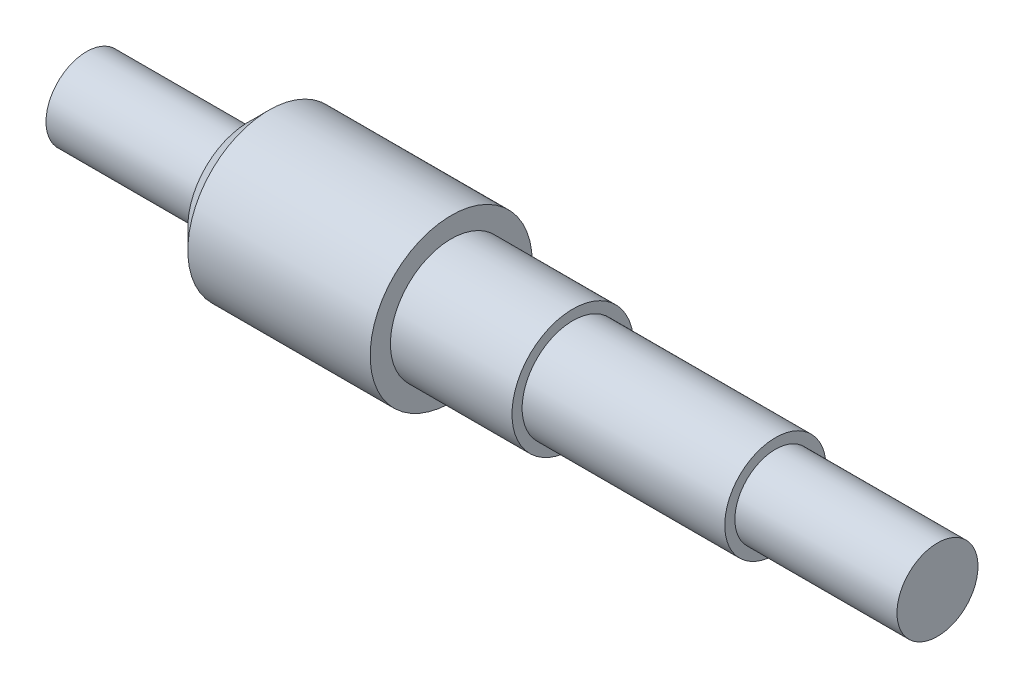
SolidWorks part; units mm, degrees
ref_plane "前视基准面" through (0, 0, 0) normal (0, 0, 1) x (1, 0, 0)
ref_plane "上视基准面" through (0, 0, 0) normal (0, 1, 0) x (1, 0, 0)
ref_plane "右视基准面" through (0, 0, 0) normal (1, 0, 0) x (0, 0, -1)
sketch "草图1" plane through (0, 0, 0) normal (1, 0, 0) x (0, 0, -1)
  circle A0 centre (0, 0) radius 4
  dimension "D1" = 8
extrude "凸台-拉伸1" add sketch "草图1" along normal blind 10
sketch "草图2" plane through (0, 0, 0) normal (-1, 0, 0) x (0, 0, 1)
  circle A0 centre (0, 0) radius 2
  dimension "D1" = 4
extrude "凸台-拉伸2" add sketch "草图2" along normal blind 8
cosmetic thread "装饰螺纹线2"
sketch "草图3" plane through (10, 0, 0) normal (1, 0, 0) x (0, 0, -1)
  circle A0 centre (0, 0) radius 3
  dimension "D1" = 6
extrude "凸台-拉伸3" add sketch "草图3" along normal blind 16
sketch "草图4" plane through (26, 0, 0) normal (1, 0, 0) x (0, 0, -1)
  circle A0 centre (0, 0) radius 2
  dimension "D1" = 4
extrude "凸台-拉伸4" add sketch "草图4" along normal blind 8
cosmetic thread "装饰螺纹线1"
chamfer "倒角1" distance 1 angle 45 1 edges at (0, 0, -4)
sketch "草图5" plane through (26, 0, 0) normal (1, 0, 0) x (0, 0, -1)
  circle A0 centre (0, 0) radius 2.5
  circle A1 centre (0, 0) radius 3
  dimension "D1" = 6
  dimension "D2" = 5
extrude "切除-拉伸1" cut sketch "草图5" against normal blind 10
